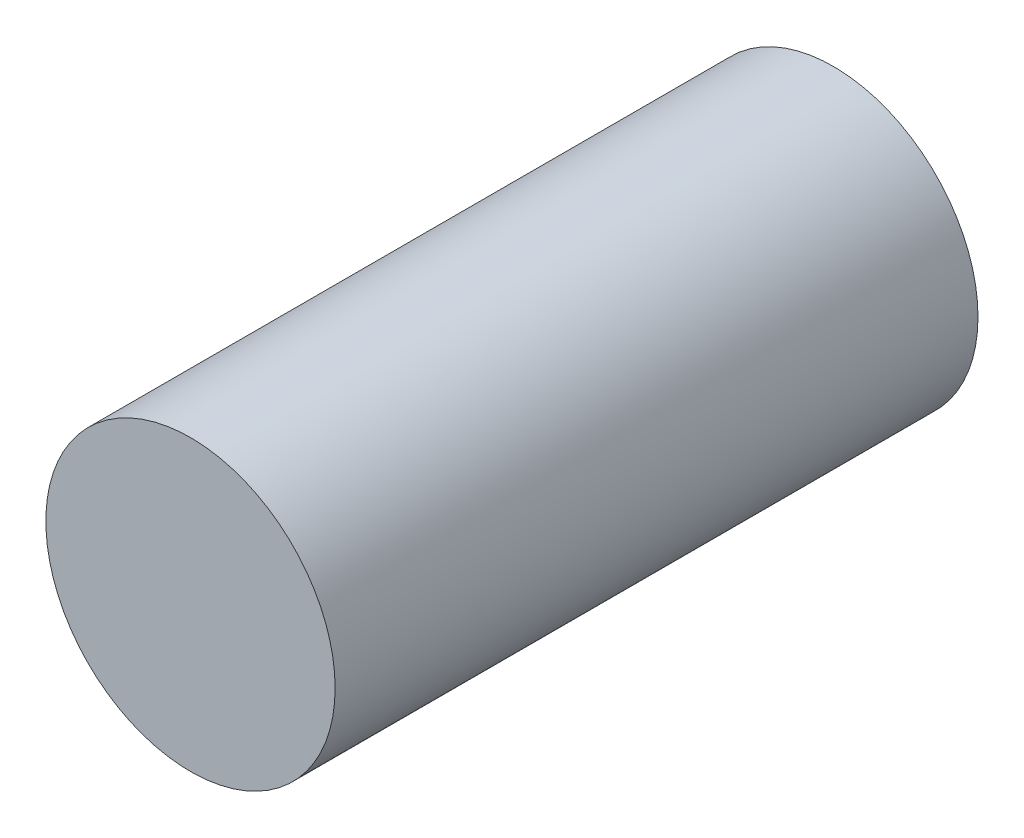
SolidWorks part; units mm, degrees
ref_plane "정면" through (0, 0, 0) normal (0, 0, 1) x (1, 0, 0)
ref_plane "윗면" through (0, 0, 0) normal (0, 1, 0) x (1, 0, 0)
ref_plane "우측면" through (0, 0, 0) normal (1, 0, 0) x (0, 0, -1)
sketch "스케치1" plane through (0, 0, 0) normal (0, 0, 1) x (1, 0, 0)
  circle A0 centre (0, 0) radius 2.25
  dimension "D1" = 4.5
extrude "보스-돌출1" add sketch "스케치1" along normal blind 10
